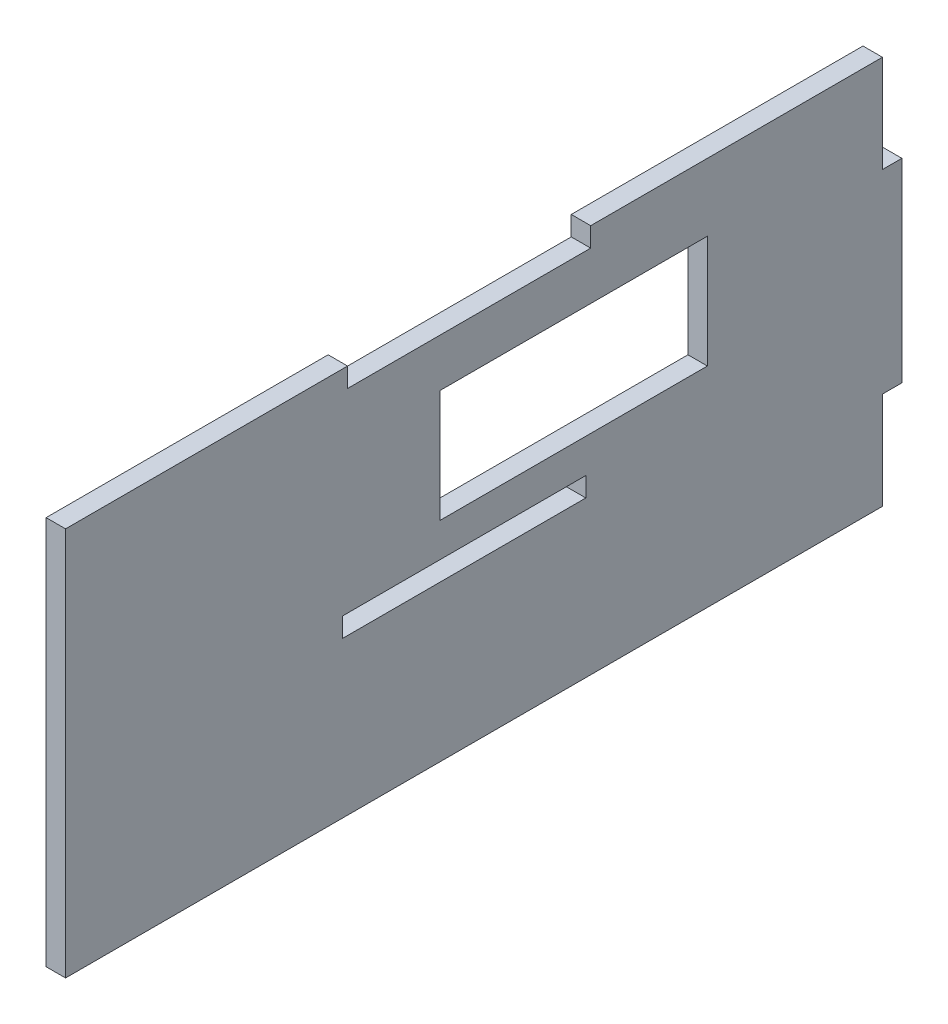
SolidWorks part; units mm, degrees
ref_plane "정면" through (0, 0, 0) normal (0, 0, 1) x (1, 0, 0)
ref_plane "윗면" through (0, 0, 0) normal (0, 1, 0) x (1, 0, 0)
ref_plane "우측면" through (0, 0, 0) normal (1, 0, 0) x (0, 0, -1)
sketch "스케치1" plane through (0, 0, 0) normal (1, 0, 0) x (0, 0, -1)
  line L1 (-87, 40) -> (87, 40)
  line L2 (-87, 40) -> (-87, -40)
  line L3 (-87, -40) -> (87, -40)
  line L4 (87, 40) -> (87, -40)
  line L5 (-87, 40) -> (87, -40) construction
  line L6 (-87, -40) -> (87, 40) construction
  point P0 (0, 0)
  dimension "D1" = 174
  dimension "D2" = 80
extrude "보스-돌출1" add sketch "스케치1" along normal blind 4
sketch "스케치3" plane through (4, 0, 0) normal (1, 0, 0) x (0, 0, -1)
  line L1 (87, 40) -> (83, 40)
  line L2 (87, 40) -> (87, 20)
  line L3 (87, 20) -> (83, 20)
  line L4 (83, 40) -> (83, 20)
  line L5 (87, -40) -> (83, -40)
  line L6 (87, -40) -> (87, -20)
  line L7 (87, -20) -> (83, -20)
  line L8 (83, -40) -> (83, -20)
  dimension "D1" = 20
  dimension "D2" = 4
  dimension "D3" = 20
  dimension "D4" = 4
extrude "컷-돌출1" cut sketch "스케치3" against normal blind 4
sketch "스케치4" plane through (4, 0, 0) normal (1, 0, 0) x (0, 0, -1)
  line L0 (83, 40) -> (-87, 40) construction
  line L1 (-27, 40) -> (23, 40)
  line L2 (-27, 40) -> (-27, 36)
  line L3 (-27, 36) -> (23, 36)
  line L4 (23, 40) -> (23, 36)
  line L5 (-87, 40) -> (-87, -40) construction
  dimension "D1" = 60
  dimension "D2" = 50
  dimension "D3" = 4
extrude "컷-돌출2" cut sketch "스케치4" against normal blind 4
sketch "스케치5" plane through (0, 0, 0) normal (-1, 0, 0) x (0, 0, 1)
  line L0 (27, 40) -> (87, 40) construction
  line L1 (87, -40) -> (85, -40)
  line L2 (87, -40) -> (87, 40)
  line L3 (87, 40) -> (85, 40)
  line L4 (85, -40) -> (85, 40)
  dimension "D1" = 2
extrude "컷-돌출3" cut sketch "스케치5" against normal blind 10
sketch "스케치8" plane through (0, 0, 0) normal (-1, 0, 0) x (0, 0, 1)
  line L0 (-83, 40) -> (-23, 40) construction
  line L1 (-22, -4) -> (28, -4)
  line L2 (-22, -4) -> (-22, -8)
  line L3 (-22, -8) -> (28, -8)
  line L4 (28, -4) -> (28, -8)
  line L5 (-87, -20) -> (-87, 20) construction
  dimension "D1" = 4
  dimension "D2" = 50
  dimension "D3" = 44
  dimension "D4" = 65
extrude "컷-돌출4" cut sketch "스케치8" against normal blind 4
sketch "스케치9" plane through (0, 0, 0) normal (-1, 0, 0) x (0, 0, 1)
  line L0 (-87, -20) -> (-87, 20) construction
  line L1 (-47, 26.1303) -> (8, 26.1303)
  line L2 (-47, 26.1303) -> (-47, 3)
  line L3 (-47, 3) -> (8, 3)
  line L4 (8, 26.1303) -> (8, 3)
  line L5 (28, -4) -> (-22, -4) construction
  dimension "D1" = 55
  dimension "D2" = 40
  dimension "D3" = 7
extrude "컷-돌출5" cut sketch "스케치9" against normal blind 4
